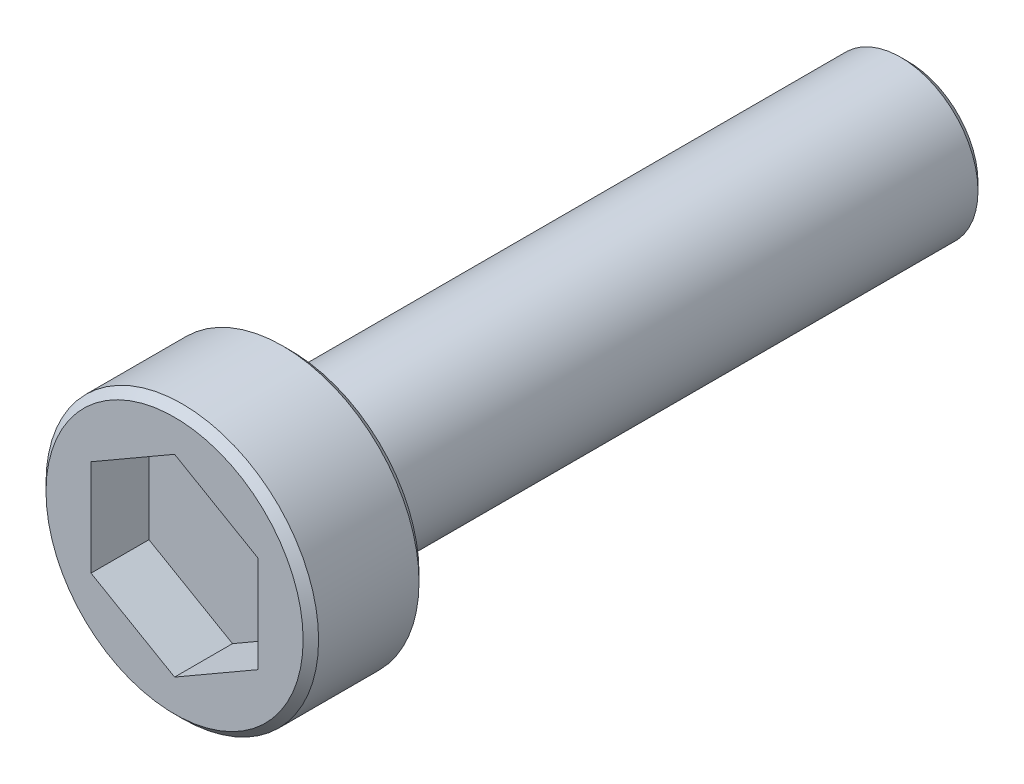
SolidWorks part; units mm, degrees
ref_plane "前视基准面" through (0, 0, 0) normal (0, 0, 1) x (1, 0, 0)
ref_plane "上视基准面" through (0, 0, 0) normal (0, 1, 0) x (1, 0, 0)
ref_plane "右视基准面" through (0, 0, 0) normal (1, 0, 0) x (0, 0, -1)
sketch "草图1" plane through (0, 0, 0) normal (0, 0, 1) x (1, 0, 0)
  circle A0 centre (0, 0) radius 2
extrude "凸台-拉伸1" add sketch "草图1" along normal blind 16
sketch "草图2" plane through (0, 0, 16) normal (0, 0, 1) x (1, 0, 0)
  circle A0 centre (0, 0) radius 3.5285
extrude "凸台-拉伸3" add sketch "草图2" along normal blind 3
sketch "草图3" plane through (0, 0, 19) normal (0, 0, 1) x (1, 0, 0)
  line L1 (0, 2.4977) -> (-2.1631, 1.2488)
  line L2 (-2.1631, 1.2488) -> (-2.1631, -1.2488)
  line L3 (-2.1631, -1.2488) -> (0, -2.4977)
  line L4 (0, -2.4977) -> (2.1631, -1.2488)
  line L5 (2.1631, -1.2488) -> (2.1631, 1.2488)
  line L6 (2.1631, 1.2488) -> (0, 2.4977)
  circle A0 centre (0, 0) radius 2.1631 construction
extrude "切除-拉伸2" cut sketch "草图3" against normal blind 1.5
chamfer "倒角1" distance 0.2 angle 45 1 edges at (2, 0, 0)
chamfer "倒角2" distance 0.2 angle 45 2 edges at (3.5285, 0, 19) (3.5285, 0, 16)
